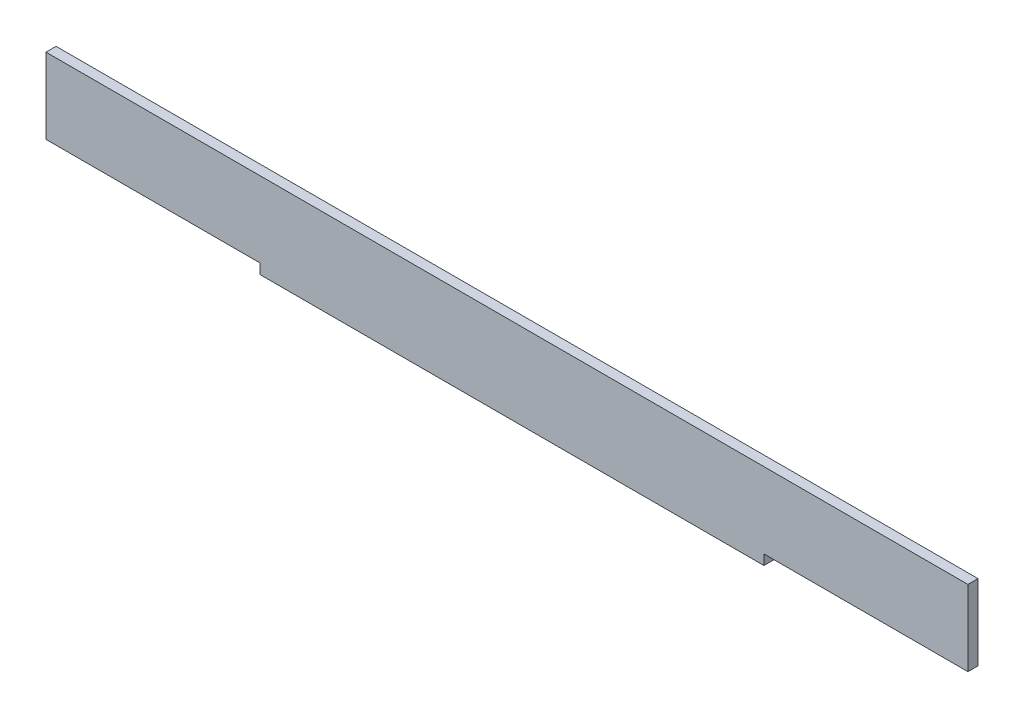
SolidWorks part; units mm, degrees
ref_plane "Front Plane" through (0, 0, 0) normal (0, 0, 1) x (1, 0, 0)
ref_plane "Top Plane" through (0, 0, 0) normal (0, 1, 0) x (1, 0, 0)
ref_plane "Right Plane" through (0, 0, 0) normal (1, 0, 0) x (0, 0, -1)
sketch "Sketch1" plane through (0, 0, 0) normal (0, 0, 1) x (1, 0, 0)
  line L0 (0, 0) -> (200, 0)
  line L1 (200, 0) -> (200, 4)
  line L2 (200, 4) -> (281, 4)
  line L3 (281, 4) -> (281, 34)
  line L4 (281, 34) -> (200, 34)
  line L5 (200, 34) -> (0, 34)
  line L6 (0, 34) -> (-85, 34)
  line L7 (-85, 34) -> (-85, 4)
  line L8 (-85, 4) -> (0, 4)
  line L9 (0, 4) -> (0, 0)
  dimension "D1" = 200
  dimension "D2" = 4
  dimension "D3" = 81
  dimension "D4" = 30
  dimension "D5" = 200
  dimension "D6" = 85
  dimension "D7" = 30
  dimension "D8" = 85
  dimension "D9" = 4
extrude "Boss-Extrude1" add sketch "Sketch1" along normal blind 4
